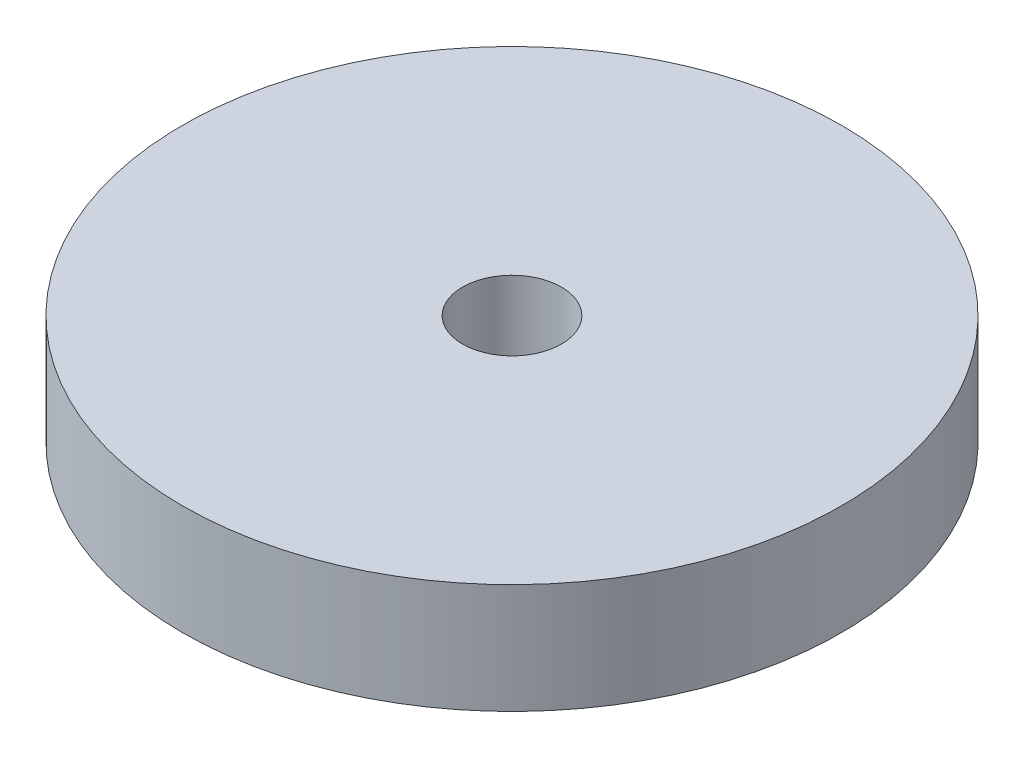
SolidWorks part; units mm, degrees
ref_plane "Front Plane" through (0, 0, 0) normal (0, 0, 1) x (1, 0, 0)
ref_plane "Top Plane" through (0, 0, 0) normal (0, 1, 0) x (1, 0, 0)
ref_plane "Right Plane" through (0, 0, 0) normal (1, 0, 0) x (0, 0, -1)
sketch "Sketch1" plane through (0, 0, 0) normal (0, 1, 0) x (1, 0, 0)
  circle A0 centre (27.633, -12.8931) radius 6
  dimension "D1" = 12
extrude "Boss-Extrude1" add sketch "Sketch1" along normal blind 2
sketch "Sketch2" plane through (0, 2, 0) normal (0, 1, 0) x (1, 0, 0)
  circle A0 centre (27.633, -12.8931) radius 0.9
  dimension "D1" = 1.8
extrude "Cut-Extrude1" cut sketch "Sketch2" against normal blind 2
